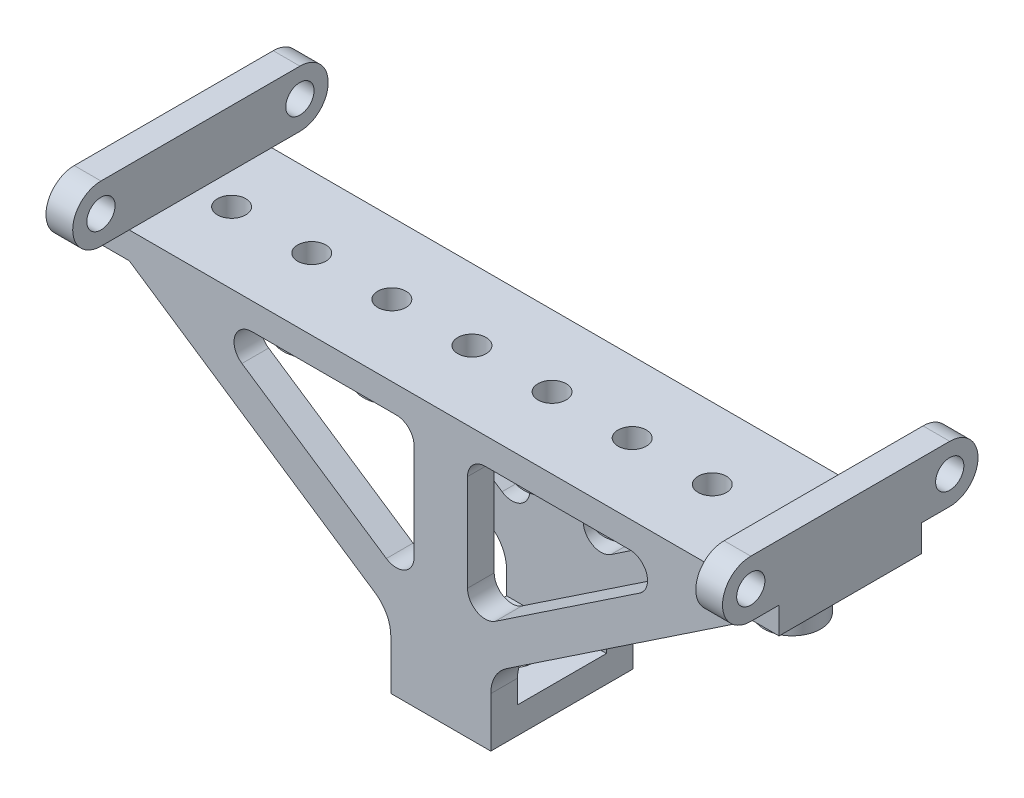
SolidWorks part; units mm, degrees
ref_plane "Front Plane" through (0, 0, 0) normal (0, 0, 1) x (1, 0, 0)
ref_plane "Top Plane" through (0, 0, 0) normal (0, 1, 0) x (1, 0, 0)
ref_plane "Right Plane" through (0, 0, 0) normal (1, 0, 0) x (0, 0, -1)
sketch "Sketch1" plane through (0, 0, 0) normal (0, 1, 0) x (1, 0, 0)
  line L0 (0, 0) -> (0, 22.2718) construction
  line L2 (35, -8) -> (-35, -8)
  line L3 (35, -8) -> (35, 8)
  line L4 (35, 8) -> (-35, 8)
  line L7 (-35, -8) -> (-35, 8)
  line L8 (35, -8) -> (-35, 8) construction
  line L9 (35, 8) -> (-35, -8) construction
  circle A0 centre (0, 0) radius 4.5 construction
  circle A1 centre (-4.5, 0) radius 1.5875
  circle A2 centre (4.5, 0) radius 1.5875
  circle A3 centre (13.5, 0) radius 1.5875
  circle A4 centre (22.5, 0) radius 1.5875
  circle A5 centre (31.5, 0) radius 1.5875
  circle A6 centre (-13.5, 0) radius 1.5875
  circle A7 centre (-22.5, 0) radius 1.5875
  circle A8 centre (-31.5, 0) radius 1.5875
  circle A9 centre (-31.5, 0) radius 9 construction
  circle A10 centre (31.5, 0) radius 9 construction
  circle A11 centre (-31.5, 0) radius 3.175 construction
  circle A12 centre (-22.5, 0) radius 3.175 construction
  circle A13 centre (-13.5, 0) radius 3.175 construction
  circle A14 centre (-4.5, 0) radius 3.175 construction
  circle A15 centre (4.5, 0) radius 3.175 construction
  circle A16 centre (13.5, 0) radius 3.175 construction
  circle A17 centre (22.5, 0) radius 3.175 construction
  circle A18 centre (31.5, 0) radius 3.175 construction
  dimension "D1" = 9
  dimension "D2" = 16
  dimension "D5" = 3.175
  dimension "D6" = 8
  dimension "D7" = 6.35
  dimension "D3" = 70
  dimension "D4" = 4
extrude "Boss-Extrude1" add sketch "Sketch1" against normal blind 3
ref_plane "Plane4" through (0, 0, -8) normal (0, 0, -1) x (-1, 0, 0)
sketch "Sketch3" plane through (0, 0, -8) normal (0, 0, -1) x (-1, 0, 0)
  line L0 (-5.615, -24.8048) -> (-5.615, -30.4)
  line L1 (-35, -3) -> (35, -3) construction
  line L2 (0, -3) -> (0, -15) construction
  line L3 (-35, -3) -> (-7.39, -21.4807)
  line L4 (5.615, -24.8048) -> (5.615, -30.4)
  line L5 (3, -5) -> (3, -15.8604)
  line L6 (35, -3) -> (7.39, -21.4807)
  line L7 (-35, -3) -> (-35, 0)
  line L8 (-35, 0) -> (35, 0)
  line L9 (-5.615, -30.4) -> (6.5395, -30.4)
  line L10 (35, 0) -> (35, -3)
  line L11 (-22.3378, -6.662) -> (-6.1125, -17.5225)
  line L12 (-21.2254, -3) -> (-5, -3)
  line L13 (-35, -3) -> (35, -3) construction
  line L14 (-3, -5) -> (-3, -15.8604)
  line L15 (21.2254, -3) -> (5, -3)
  line L16 (22.3378, -6.662) -> (6.1125, -17.5225)
  line L21 (-28.3784, -2.6188) -> (28.9505, -3.4735) construction
  line L22 (-28.3784, -2.6188) -> (-5.1651, -18.1566) construction
  line L23 (6.0896, -18.7754) -> (28.9505, -3.4735) construction
  line L24 (-1.615, -26.4) -> (2.5395, -26.4) construction
  line L26 (-35, 1.4804) -> (35, 0.4367) construction
  line L27 (-35, 1.4804) -> (-35, -3) construction
  line L28 (35, 0.4367) -> (35, -4.2376) construction
  line L29 (28.9505, -3.4735) -> (28.9505, -3.4735) construction
  line L30 (-28.3784, -2.6188) -> (-28.3784, -2.6188) construction
  line L31 (8.3145, -22.0995) -> (35, -4.2376) construction
  line L32 (6.5395, -25.4236) -> (6.5395, -30.4) construction
  line L33 (-1.615, -24.8048) -> (-1.615, -26.4) construction
  line L34 (2.5395, -25.4236) -> (2.5395, -26.4) construction
  circle A0 centre (0, -3) radius 12 construction
  circle A1 centre (0, -15) radius 5 construction
  arc A2 (-5.615, -24.8048) -> (-7.39, -21.4807) centre (-9.615, -24.8048) ccw
  arc A3 (5.615, -24.8048) -> (7.39, -21.4807) centre (9.615, -24.8048) cw
  arc A4 (-3, -5) -> (-5, -3) centre (-5, -5) ccw
  circle A5 centre (0, 0) radius 3 construction
  arc A6 (-22.3378, -6.662) -> (-21.2254, -3) centre (-21.2254, -5) cw
  arc A7 (3, -15.8604) -> (6.1125, -17.5225) centre (5, -15.8604) ccw
  arc A8 (2.5395, -25.4236) -> (6.0896, -18.7754) centre (10.5395, -25.4236) cw construction
  arc A9 (-1.615, -24.8048) -> (-5.1651, -18.1566) centre (-9.615, -24.8048) ccw construction
  arc A10 (6.5395, -25.4236) -> (8.3145, -22.0995) centre (10.5395, -25.4236) cw construction
  arc A11 (-3, -15.8604) -> (-6.1125, -17.5225) centre (-5, -15.8604) cw
  arc A12 (22.3378, -6.662) -> (21.2254, -3) centre (21.2254, -5) ccw
  arc A13 (3, -5) -> (5, -3) centre (5, -5) cw
  point P14 (-5, -15)
  point P20 (5, -15)
  dimension "D1" = 4
  dimension "D2" = 2
  dimension "D3" = 4
  dimension "D5" = 21.2254
  dimension "D6" = 2
  dimension "D7" = 2
  dimension "D4" = 27.4
extrude "Boss-Extrude6" add sketch "Sketch3" against normal blind 3
ref_plane "Plane6" through (0, 0, 8) normal (0, 0, 1) x (1, 0, 0)
sketch "Sketch6" plane through (0, 0, 8) normal (0, 0, 1) x (1, 0, 0)
  line L0 (-5.615, -24.8048) -> (-5.615, -30.4)
  line L2 (0, -3) -> (0, -15) construction
  line L3 (-35, -3) -> (-7.39, -21.4807)
  line L4 (5.615, -24.8048) -> (5.615, -30.4)
  line L5 (3, -5) -> (3, -15.8604)
  line L6 (35, -3) -> (7.39, -21.4807)
  line L7 (-35, -3) -> (-35, 0)
  line L8 (-35, 0) -> (35, 0)
  line L9 (-5.615, -30.4) -> (6.5395, -30.4)
  line L10 (35, 0) -> (35, -3)
  line L11 (-22.3378, -6.662) -> (-6.1125, -17.5225)
  line L12 (-21.2254, -3) -> (-5, -3)
  line L13 (-35, -3) -> (35, -3) construction
  line L14 (-3, -5) -> (-3, -15.8604)
  line L15 (21.2254, -3) -> (5, -3)
  line L16 (22.3378, -6.662) -> (6.1125, -17.5225)
  line L21 (-28.3784, -2.6188) -> (28.9505, -3.4735) construction
  line L22 (-28.3784, -2.6188) -> (-5.1651, -18.1566) construction
  line L23 (6.0896, -18.7754) -> (28.9505, -3.4735) construction
  line L24 (-1.615, -26.4) -> (2.5395, -26.4) construction
  line L26 (-35, 1.4804) -> (35, 0.4367) construction
  line L27 (-35, 1.4804) -> (-35, -3) construction
  line L28 (35, 0.4367) -> (35, -4.2376) construction
  line L29 (28.9505, -3.4735) -> (28.9505, -3.4735) construction
  line L30 (-28.3784, -2.6188) -> (-28.3784, -2.6188) construction
  line L31 (8.3145, -22.0995) -> (35, -4.2376) construction
  line L32 (6.5395, -25.4236) -> (6.5395, -30.4) construction
  line L33 (-1.615, -24.8048) -> (-1.615, -26.4) construction
  line L34 (2.5395, -25.4236) -> (2.5395, -26.4) construction
  circle A0 centre (0, -3) radius 12 construction
  circle A1 centre (0, -15) radius 5 construction
  arc A2 (-5.615, -24.8048) -> (-7.39, -21.4807) centre (-9.615, -24.8048) ccw
  arc A3 (5.615, -24.8048) -> (7.39, -21.4807) centre (9.615, -24.8048) cw
  arc A4 (-3, -5) -> (-5, -3) centre (-5, -5) ccw
  circle A5 centre (0, 0) radius 3 construction
  arc A6 (-22.3378, -6.662) -> (-21.2254, -3) centre (-21.2254, -5) cw
  arc A7 (3, -15.8604) -> (6.1125, -17.5225) centre (5, -15.8604) ccw
  arc A8 (2.5395, -25.4236) -> (6.0896, -18.7754) centre (10.5395, -25.4236) cw construction
  arc A9 (-1.615, -24.8048) -> (-5.1651, -18.1566) centre (-9.615, -24.8048) ccw construction
  arc A10 (6.5395, -25.4236) -> (8.3145, -22.0995) centre (10.5395, -25.4236) cw construction
  arc A11 (-3, -15.8604) -> (-6.1125, -17.5225) centre (-5, -15.8604) cw
  arc A12 (22.3378, -6.662) -> (21.2254, -3) centre (21.2254, -5) ccw
  arc A13 (3, -5) -> (5, -3) centre (5, -5) cw
  point P14 (-5, -15)
  point P20 (5, -15)
  dimension "D1" = 4
  dimension "D2" = 2
  dimension "D3" = 4
  dimension "D5" = 21.2254
  dimension "D6" = 2
  dimension "D7" = 2
  dimension "D4" = 27.4
extrude "Boss-Extrude9" add sketch "Sketch6" against normal blind 3 contours L4 A3 L6 L10 L8 L7 L3 A2 L0 L9 L14 A11 L11 A6 L12 A4 L5 A13 L15 A12 L16 A7
ref_plane "Plane9" through (0, -30.4, 0) normal (0, -1, 0) x (1, 0, 0)
sketch "Sketch7" plane through (0, -30.4, 0) normal (0, -1, 0) x (1, 0, 0)
  line L0 (16.72, 8) -> (-16.72, 8) construction
  line L1 (-5.5982, 8) -> (5.615, 8)
  line L2 (-5.5982, 8) -> (-5.5982, -8)
  line L3 (-5.5982, -8) -> (5.615, -8)
  line L4 (5.615, 8) -> (5.615, -8)
  line L5 (-14.0394, -8) -> (14.0394, -8) construction
  line L6 (5.615, -5) -> (5.615, -8) construction
  circle A0 centre (0, 0) radius 2.413
  circle A1 centre (0, 0) radius 4.7625 construction
  dimension "D1" = 4.826
extrude "Boss-Extrude10" add sketch "Sketch7" against normal blind 3
ref_plane "Plane11" through (35, 0, 0) normal (1, 0, 0) x (0, 0, -1)
sketch "Sketch10" plane through (35, 0, 0) normal (1, 0, 0) x (0, 0, -1)
  line L2 (-11.175, 0) -> (-8, 0)
  line L3 (0, 0) -> (0, 6.35) construction
  line L4 (-11.175, 6.35) -> (-11.175, 0) construction
  line L5 (11.175, 6.35) -> (-11.175, 6.35)
  line L6 (-8, 16.72) -> (-8, -16.72) construction
  line L7 (-8, 0) -> (-8, -3)
  line L8 (-8, -3) -> (-5, -3) construction
  line L9 (-8, -3) -> (8, -3)
  line L10 (8, -16.7201) -> (8, 16.7201) construction
  line L11 (8, -3) -> (8, 0)
  line L12 (8, 0) -> (11.175, 0)
  circle A0 centre (11.175, 3.175) radius 1.5875
  arc A1 (-11.175, 6.35) -> (-11.175, 0) centre (-11.175, 3.175) ccw
  arc A2 (11.175, 6.35) -> (11.175, 0) centre (11.175, 3.175) cw
  circle A6 centre (-11.175, 3.175) radius 1.5875
extrude "Boss-Extrude11" add sketch "Sketch10" along normal blind 3
ref_plane "Plane12" through (-35, 0, 0) normal (-1, 0, 0) x (0, 0, 1)
sketch "Sketch11" plane through (-35, 0, 0) normal (-1, 0, 0) x (0, 0, 1)
  line L2 (-11.175, 0) -> (-8, 0)
  line L3 (0, 0) -> (0, 6.35) construction
  line L4 (-11.175, 6.35) -> (-11.175, 0) construction
  line L5 (11.175, 6.35) -> (-11.175, 6.35)
  line L7 (-8, 0) -> (-8, -3)
  line L9 (-8, -3) -> (8, -3)
  line L11 (8, -3) -> (8, 0)
  line L12 (8, 0) -> (11.175, 0)
  circle A0 centre (11.175, 3.175) radius 1.5875
  arc A1 (-11.175, 6.35) -> (-11.175, 0) centre (-11.175, 3.175) ccw
  arc A2 (11.175, 6.35) -> (11.175, 0) centre (11.175, 3.175) cw
  circle A6 centre (-11.175, 3.175) radius 1.5875
extrude "Boss-Extrude12" add sketch "Sketch11" along normal blind 3
ref_plane "Plane13" through (0, -3, 0) normal (0, -1, 0) x (1, 0, 0)
sketch "Sketch12" plane through (0, -3, 0) normal (0, -1, 0) x (1, 0, 0)
  line L0 (0, 0) -> (0, 22.2718) construction
  line L8 (35, -8) -> (-35, 8) construction
  line L9 (35, 8) -> (-35, -8) construction
  circle A0 centre (0, 0) radius 4.5 construction
  circle A1 centre (-4.5, 0) radius 1.5875
  circle A2 centre (4.5, 0) radius 1.5875
  circle A3 centre (13.5, 0) radius 1.5875
  circle A4 centre (22.5, 0) radius 1.5875
  circle A5 centre (31.5, 0) radius 1.5875
  circle A6 centre (-13.5, 0) radius 1.5875
  circle A7 centre (-22.5, 0) radius 1.5875
  circle A8 centre (-31.5, 0) radius 1.5875
  circle A9 centre (-31.5, 0) radius 9 construction
  circle A10 centre (31.5, 0) radius 9 construction
  circle A11 centre (-31.5, 0) radius 3.175
  circle A12 centre (-22.5, 0) radius 3.175
  circle A13 centre (-13.5, 0) radius 3.175
  circle A14 centre (-4.5, 0) radius 3.175
  circle A15 centre (4.5, 0) radius 3.175
  circle A16 centre (13.5, 0) radius 3.175
  circle A17 centre (22.5, 0) radius 3.175
  circle A18 centre (31.5, 0) radius 3.175
  dimension "D1" = 9
  dimension "D2" = 16
  dimension "D5" = 3.175
  dimension "D6" = 8
  dimension "D7" = 6.35
  dimension "D3" = 70
  dimension "D4" = 4
extrude "Boss-Extrude13" add sketch "Sketch12" along normal blind 5
